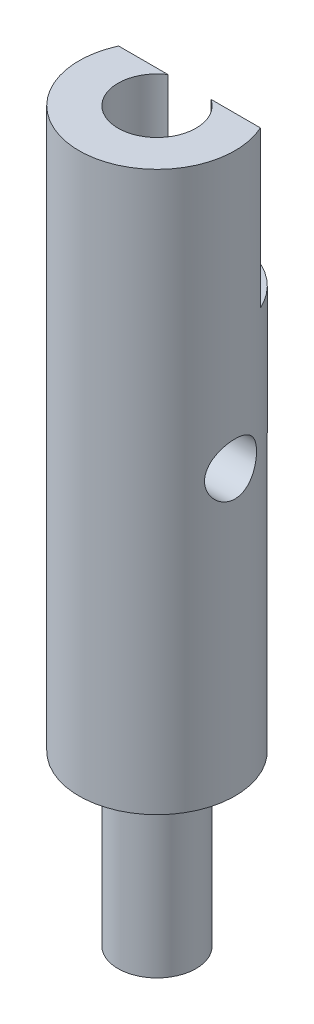
SolidWorks part; units mm, degrees
material "1060 合金"
ref_plane "Front" through (0, 0, 0) normal (0, 0, 1) x (1, 0, 0)
ref_plane "Top" through (0, 0, 0) normal (0, 1, 0) x (1, 0, 0)
ref_plane "Right" through (0, 0, 0) normal (1, 0, 0) x (0, 0, -1)
sketch "ｽｹｯﾁ1" plane through (0, 0, 0) normal (0, 1, 0) x (1, 0, 0)
  circle A2 centre (0, 0) radius 6
  dimension "D1" = 12
extrude "ﾎﾞｽ - 押し出し1" add sketch "ｽｹｯﾁ1" along normal blind 56
sketch "ｽｹｯﾁ2" plane through (0, 56, 0) normal (0, 1, 0) x (1, 0, 0)
  line L0 (5.4544, 2.5) -> (-5.4544, 2.5)
  circle A0 centre (0, 0) radius 6
  circle A1 centre (0, 0) radius 3
  circle M2 centre (0, 0) radius 6
  dimension "D1" = 6
  dimension "D2" = 12
  dimension "D3" = 2.5
extrude "ｶｯﾄ - 押し出し1" cut sketch "ｽｹｯﾁ2" against normal blind 12 contours L0 A1 | A1 L0 M2 | L0 A1
sketch "ｽｹｯﾁ3" plane through (0, 0, 0) normal (0, -1, 0) x (1, 0, 0)
  circle A0 centre (0, 0) radius 6
  circle A1 centre (0, 0) radius 3
  dimension "D1" = 6
  dimension "D2" = 12
extrude "ｶｯﾄ - 押し出し2" cut sketch "ｽｹｯﾁ3" against normal blind 13
sketch "ｽｹｯﾁ6" plane through (0, 0, 0) normal (1, 0, 0) x (0, 0, -1)
  line L0 (0, 0) -> (0, 50.0006) construction
  line L1 (-3, 0) -> (3, 0) construction
  circle A0 centre (0, 34.8) radius 2
  dimension "D1" = 4
  dimension "D2" = 34.8
  dimension "D3" = 6
extrude "ｶｯﾄ - 押し出し6" cut sketch "ｽｹｯﾁ6" against normal through all both and the other way through all
